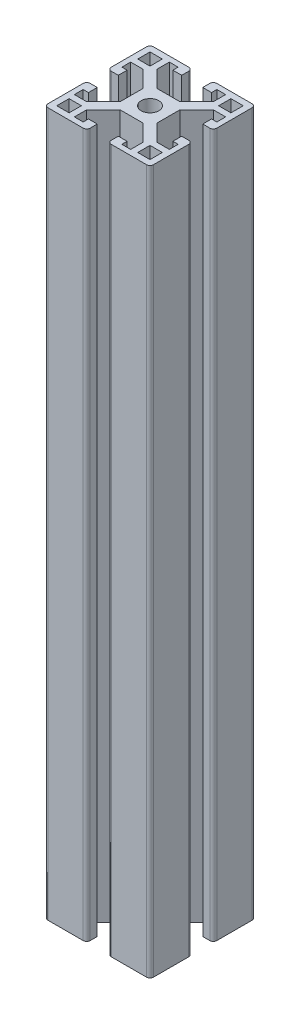
SolidWorks part; units mm, degrees
material "1060 Alloy"
ref_plane "Front Plane" through (0, 0, 0) normal (0, 0, 1) x (1, 0, 0)
ref_plane "Top Plane" through (0, 0, 0) normal (0, 1, 0) x (1, 0, 0)
ref_plane "Right Plane" through (0, 0, 0) normal (1, 0, 0) x (0, 0, -1)
sketch "Sketch1" plane through (0, 0, 0) normal (0, 1, 0) x (1, 0, 0)
  line L0 (-15, 7.5) -> (-15, -4.5)
  line L1 (-15, 7.5) -> (15, 7.5) construction
  line L2 (-15, 7.5) -> (-15, -7.5) construction
  line L3 (-15, -7.5) -> (15, -7.5) construction
  line L4 (15, 7.5) -> (15, -7.5) construction
  line L5 (0, -7.5) -> (0, 7.5) construction
  line L6 (-15, 0) -> (15, 0) construction
  line L7 (-15, 7.5) -> (-3, 7.5)
  line L8 (-15, -4.5) -> (-12, -4.5)
  line L9 (-12, -4.5) -> (-12, -2)
  line L10 (-12, -2) -> (-13.5, -2)
  line L11 (-13.5, -2) -> (-13.5, 0.5)
  line L12 (-13.5, 0.5) -> (-10, 0.5)
  line L13 (-5.25, -2.25) -> (5.25, -2.25) construction
  line L14 (-5.25, -2.25) -> (-5.25, -12.75) construction
  line L15 (-5.25, -12.75) -> (5.25, -12.75) construction
  line L16 (5.25, -2.25) -> (5.25, -12.75) construction
  line L17 (0, -12.75) -> (0, -2.25) construction
  line L18 (-5.25, -7.5) -> (5.25, -7.5) construction
  line L19 (-2.5857, -4.9143) -> (-15, 7.5) construction
  line L20 (-10, 0.5) -> (-5.25, -4.25)
  line L21 (-8, 2.5) -> (-3.25, -2.25)
  line L22 (-3, 7.5) -> (-3, 4.5)
  line L23 (-3, 4.5) -> (-5.5, 4.5)
  line L24 (-5.5, 4.5) -> (-5.5, 6)
  line L25 (-5.5, 6) -> (-8, 6)
  line L26 (-8, 6) -> (-8, 2.5)
  line L27 (5.5, 4.5) -> (5.5, 6)
  line L28 (-13.25, 5.75) -> (-9.75, 5.75)
  line L29 (-13.25, 5.75) -> (-13.25, 2.25)
  line L30 (-13.25, 2.25) -> (-9.75, 2.25)
  line L31 (-9.75, 5.75) -> (-9.75, 2.25)
  line L32 (-11.5, 2.25) -> (-11.5, 5.75) construction
  line L33 (-13.25, 4) -> (-9.75, 4) construction
  line L34 (13.25, 2.25) -> (9.75, 2.25)
  line L35 (13.25, 5.75) -> (13.25, 2.25)
  line L36 (13.25, 5.75) -> (9.75, 5.75)
  line L37 (9.75, 5.75) -> (9.75, 2.25)
  line L38 (3, 4.5) -> (5.5, 4.5)
  line L39 (3, 7.5) -> (3, 4.5)
  line L40 (5.5, 6) -> (8, 6)
  line L41 (8, 6) -> (8, 2.5)
  line L42 (15, 7.5) -> (3, 7.5)
  line L43 (13.5, 0.5) -> (10, 0.5)
  line L44 (13.5, -2) -> (13.5, 0.5)
  line L45 (12, -2) -> (13.5, -2)
  line L46 (15, 7.5) -> (15, -4.5)
  line L47 (15, -4.5) -> (12, -4.5)
  line L48 (12, -4.5) -> (12, -2)
  line L49 (8, 2.5) -> (3.25, -2.25)
  line L50 (10, 0.5) -> (5.25, -4.25)
  line L51 (-5.25, -4.25) -> (-5.25, -10.75)
  line L52 (-3.25, -2.25) -> (3.25, -2.25)
  line L53 (5.25, -4.25) -> (5.25, -10.75)
  line L54 (15, -22.5) -> (15, -10.5)
  line L55 (15, -10.5) -> (12, -10.5)
  line L56 (12, -10.5) -> (12, -13)
  line L57 (12, -13) -> (13.5, -13)
  line L58 (13.5, -13) -> (13.5, -15.5)
  line L59 (13.5, -15.5) -> (10, -15.5)
  line L60 (13.25, -17.25) -> (9.75, -17.25)
  line L61 (13.25, -20.75) -> (13.25, -17.25)
  line L62 (13.25, -20.75) -> (9.75, -20.75)
  line L63 (9.75, -20.75) -> (9.75, -17.25)
  line L64 (8, -21) -> (8, -17.5)
  line L65 (5.5, -21) -> (8, -21)
  line L66 (5.5, -19.5) -> (5.5, -21)
  line L67 (15, -22.5) -> (3, -22.5)
  line L68 (3, -22.5) -> (3, -19.5)
  line L69 (3, -19.5) -> (5.5, -19.5)
  line L70 (10, -15.5) -> (5.25, -10.75)
  line L71 (8, -17.5) -> (3.25, -12.75)
  line L72 (-3, -22.5) -> (-3, -19.5)
  line L73 (-3, -19.5) -> (-5.5, -19.5)
  line L74 (-5.5, -19.5) -> (-5.5, -21)
  line L75 (-5.5, -21) -> (-8, -21)
  line L76 (-8, -21) -> (-8, -17.5)
  line L77 (-15, -22.5) -> (-3, -22.5)
  line L78 (-9.75, -20.75) -> (-9.75, -17.25)
  line L79 (-13.25, -20.75) -> (-9.75, -20.75)
  line L80 (-13.25, -20.75) -> (-13.25, -17.25)
  line L81 (-13.25, -17.25) -> (-9.75, -17.25)
  line L82 (-13.5, -15.5) -> (-10, -15.5)
  line L83 (-13.5, -13) -> (-13.5, -15.5)
  line L84 (-12, -13) -> (-13.5, -13)
  line L85 (-15, -22.5) -> (-15, -10.5)
  line L86 (-15, -10.5) -> (-12, -10.5)
  line L87 (-12, -10.5) -> (-12, -13)
  line L88 (-3.25, -12.75) -> (3.25, -12.75)
  line L89 (-8, -17.5) -> (-3.25, -12.75)
  line L90 (-10, -15.5) -> (-5.25, -10.75)
  circle A0 centre (0, -7.5) radius 2.5
  point P0 (0, 0)
  point P18 (-11.5, 4)
  dimension "D7" = 1.5
  dimension "D19" = 5
  dimension "D1" = 30
  dimension "D2" = 15
  dimension "D3" = 12
  dimension "D4" = 12
  dimension "D5" = 3
  dimension "D6" = 2.5
  dimension "D8" = 2.5
  dimension "D9" = 10.5
  dimension "D10" = 3.5
  dimension "D11" = 45
  dimension "D12" = 3
  dimension "D13" = 2.5
  dimension "D14" = 1.5
  dimension "D15" = 2.5
  dimension "D16" = 3.5
  dimension "D17" = 3.5
  dimension "D18" = 3.5
extrude "Boss-Extrude1" add sketch "Sketch1" against normal blind 200
fillet "Fillet1" radius 1 12 edges at (-3, -100, -7.5) (-15, -100, -7.5) (-15, -100, 4.5) (3, -100, -7.5) (15, -100, 4.5) (15, -100, -7.5) (-15, -100, 10.5) (15, -100, 10.5) (3, -100, 22.5) (-3, -100, 22.5) (-15, -100, 22.5) (15, -100, 22.5)
